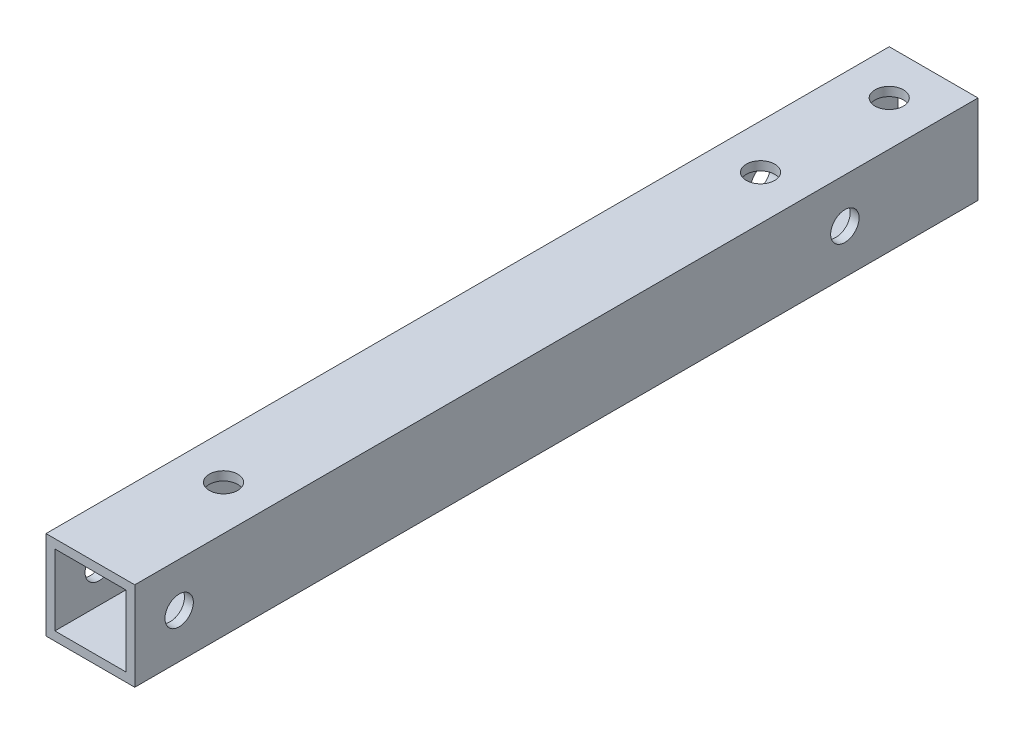
SolidWorks part; units mm, degrees
ref_plane "正面" through (0, 0, 0) normal (0, 0, 1) x (1, 0, 0)
ref_plane "平面" through (0, 0, 0) normal (0, 1, 0) x (1, 0, 0)
ref_plane "右側面" through (0, 0, 0) normal (1, 0, 0) x (0, 0, -1)
sketch "ｽｹｯﾁ1" plane through (0, 0, 0) normal (0, 0, 1) x (1, 0, 0)
  line L1 (-5, 5) -> (5, 5)
  line L2 (-5, 5) -> (-5, -5)
  line L3 (-5, -5) -> (5, -5)
  line L4 (5, 5) -> (5, -5)
  line L5 (-5, 5) -> (5, -5) construction
  line L6 (-5, -5) -> (5, 5) construction
  line L7 (-4, 4) -> (4, 4)
  line L8 (-4, 4) -> (-4, -4)
  line L9 (-4, -4) -> (4, -4)
  line L10 (4, 4) -> (4, -4)
  line L11 (-4, 4) -> (4, -4) construction
  line L12 (-4, -4) -> (4, 4) construction
  point P0 (0, 0)
  point P6 (0, 0)
  dimension "D1" = 10
  dimension "D2" = 10
  dimension "D3" = 8
  dimension "D4" = 8
extrude "ﾎﾞｽ - 押し出し1" add sketch "ｽｹｯﾁ1" along normal blind 95
sketch "ｽｹｯﾁ2" plane through (0, 5, 0) normal (0, 1, 0) x (1, 0, 0)
  line L0 (0, -5.5) -> (0, 5.5) construction
  line L1 (5, -95) -> (-5, -95) construction
  line L2 (-5.5, 0) -> (5.5, 0) construction
  circle A0 centre (0, -5) radius 1.6
  circle A1 centre (0, -80) radius 1.6
  circle A2 centre (0, -19.5) radius 1.6
  dimension "D1" = 3.2
  dimension "D2" = 15
  dimension "D3" = 3.2
  dimension "D5" = 3.2
  dimension "D6" = 14.5
  dimension "D4" = 5
extrude "ｶｯﾄ - 押し出し1" cut sketch "ｽｹｯﾁ2" against normal through all
sketch "ｽｹｯﾁ3" plane through (-5, 0, 0) normal (-1, 0, 0) x (0, 0, 1)
  line L0 (5.5, 0) -> (-5.5, 0) construction
  line L1 (0, -5.5) -> (0, 5.5) construction
  line L2 (95, 5) -> (95, -5) construction
  circle A0 centre (15, 0) radius 1.6
  circle A1 centre (90, 0) radius 1.6
  dimension "D1" = 3.2
  dimension "D2" = 15
  dimension "D3" = 3.2
  dimension "D4" = 5
extrude "ｶｯﾄ - 押し出し2" cut sketch "ｽｹｯﾁ3" against normal through all
equation "\"pipelength\" = 95"
equation "\"D1@ﾎﾞｽ - 押し出し1\"=\"pipelength\""
